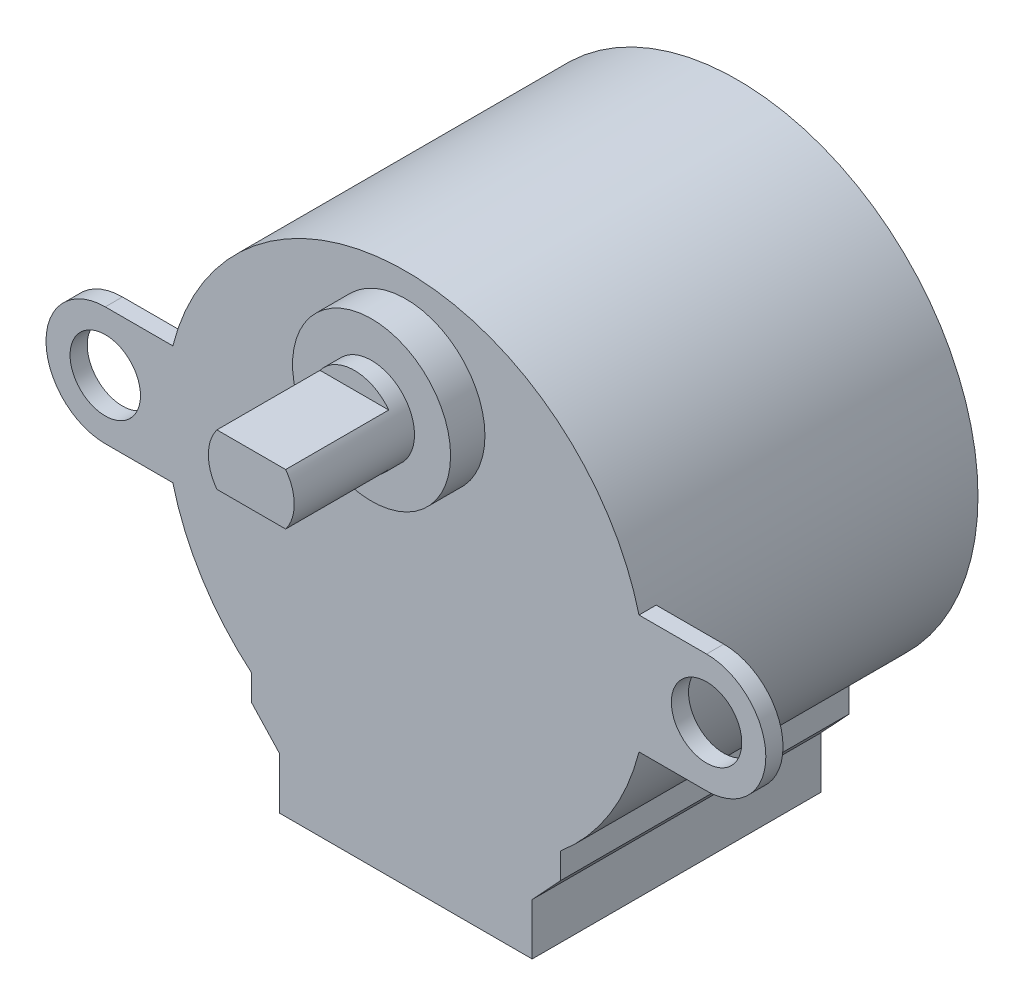
SolidWorks part; units mm, degrees
material "Air"
ref_plane "Front Plane" through (0, 0, 0) normal (0, 0, 1) x (1, 0, 0)
ref_plane "Top Plane" through (0, 0, 0) normal (0, 1, 0) x (1, 0, 0)
ref_plane "Right Plane" through (0, 0, 0) normal (1, 0, 0) x (0, 0, -1)
sketch "Sketch1" plane through (0, 0, 0) normal (0, 0, 1) x (1, 0, 0)
  circle A0 centre (0, 0) radius 14
  dimension "D1" = 28
extrude "Boss-Extrude1" add sketch "Sketch1" along normal blind 19.3
sketch "Sketch3" plane through (0, 0, 19.3) normal (0, 0, 1) x (1, 0, 0)
  line L0 (672.6511, 1264.4521) -> (697.6511, 1264.4521) construction
  line L1 (-576.9945, 40.9982) -> (-576.9945, 65.9982) construction
  dimension "D1" = 25
  dimension "D2" = 25
sketch "Sketch2" plane through (0, 0, 19.3) normal (0, 0, 1) x (1, 0, 0)
  line L0 (-7.35, -17) -> (7.35, -17)
  line L1 (7.35, -17) -> (7.35, -14)
  line L2 (7.35, -14) -> (9, -12.2238)
  line L3 (9, -12.2238) -> (9, -10.7238)
  line L4 (-7.35, -17) -> (-7.35, -14)
  line L5 (-7.35, -14) -> (-9, -12.2238)
  line L6 (-9, -12.2238) -> (-9, -10.7238)
  line L7 (9, -10.7238) -> (-9, -10.7238) construction
  circle A0 centre (0, 0) radius 14 construction
  arc A1 (-9, -10.7238) -> (9, -10.7238) centre (0, 0) ccw
  point P2 (0, -17)
  dimension "D1" = 14.7
  dimension "D2" = 17
  dimension "D3" = 18
  dimension "D4" = 3
  dimension "D5" = 3
  dimension "D6" = 1.5
  dimension "D7" = 1.5
extrude "Boss-Extrude2" add sketch "Sketch2" against normal blind 16.8 contours L1 L2 L3 A1 L6 L5 L4 L0
sketch "Sketch4" plane through (0, -17, 0) normal (0, -1, 0) x (1, 0, 0)
  line L0 (-3, 17.55) -> (3, 17.55) construction
  line L1 (-3, 18.05) -> (3, 18.05)
  line L2 (-3, 17.05) -> (3, 17.05)
  line L3 (-7.35, 19.3) -> (7.35, 19.3) construction
  arc A0 (-3, 18.05) -> (-3, 17.05) centre (-3, 17.55) ccw
  arc A1 (3, 17.05) -> (3, 18.05) centre (3, 17.55) ccw
  point P2 (0, 17.55)
  dimension "D1" = 6
  dimension "D2" = 0.5
  dimension "D3" = 1.75
extrude "Cut-Extrude1" cut sketch "Sketch4" against normal blind 2
sketch "Sketch5" plane through (0, 0, 19.3) normal (0, 0, 1) x (1, 0, 0)
  line L0 (0, 14) -> (0, -18.7354) construction
  line L1 (0, 0) -> (9.5563, 0) construction
  line L2 (-17.5, 3.45) -> (-13.5683, 3.45)
  line L3 (-17.5, -3.45) -> (-13.5683, -3.45)
  line L4 (17.5, -3.45) -> (13.5683, -3.45)
  line L5 (17.5, 3.45) -> (13.5683, 3.45)
  circle A0 centre (-17.5, 0) radius 2.05
  arc A3 (-17.5, 3.45) -> (-17.5, -3.45) centre (-17.5, 0) ccw
  arc A4 (9, -10.7238) -> (-9, -10.7238) centre (0, 0) ccw construction
  arc A5 (13.5683, 3.45) -> (13.5683, -3.45) centre (0, 0) cw
  arc A6 (-13.5683, 3.45) -> (-13.5683, -3.45) centre (0, 0) ccw
  arc A7 (17.5, 3.45) -> (17.5, -3.45) centre (17.5, 0) cw
  circle A8 centre (17.5, 0) radius 2.05
  dimension "D1" = 4.1
  dimension "D3" = 6.9
extrude "Boss-Extrude3" add sketch "Sketch5" against normal blind 1
sketch "Sketch6" plane through (0, 0, 19.3) normal (0, 0, 1) x (1, 0, 0)
  line L0 (-24.9917, 0) -> (30.299, 0) construction
  line L1 (0, 14.8773) -> (0, -18.0753) construction
  circle A0 centre (0, 8) radius 4.6
  dimension "D1" = 9.2
  dimension "D2" = 8
extrude "Boss-Extrude4" add sketch "Sketch6" along normal blind 2
sketch "Sketch7" plane through (0, 0, 21.3) normal (0, 0, 1) x (1, 0, 0)
  circle A0 centre (0, 8) radius 2.5
  dimension "D1" = 5
extrude "Boss-Extrude5" add sketch "Sketch7" along normal blind 7
sketch "Sketch8" plane through (0, 0, 28.3) normal (0, 0, 1) x (1, 0, 0)
  line L0 (-2, 9.5) -> (2, 9.5)
  line L1 (-2, 6.5) -> (2, 6.5)
  line L2 (0, 9.5) -> (0, 6.5) construction
  circle A0 centre (0, 8) radius 2.5
  point P9 (0, 8)
  circle M4 centre (0, 8) radius 2.5
  dimension "D2" = 5
  dimension "D1" = 3
extrude "Cut-Extrude2" cut sketch "Sketch8" against normal blind 6 contours L0 M4 | L1 M4
sketch "Sketch9" plane through (0, 0, 19.3) normal (0, 0, 1) x (1, 0, 0)
  line L11 (13.5683, -3.45) -> (17.5, -3.45)
  line L12 (17.5, 3.45) -> (13.5683, 3.45)
  line L13 (-13.5683, 3.45) -> (-17.5, 3.45)
  line L14 (-17.5, -3.45) -> (-13.5683, -3.45)
  line L15 (-9, -10.7238) -> (-9, -12.2238)
  line L16 (-9, -12.2238) -> (-7.35, -14)
  line L17 (-7.35, -14) -> (-7.35, -17)
  line L18 (-7.35, -17) -> (7.35, -17)
  line L19 (7.35, -17) -> (7.35, -14)
  line L20 (7.35, -14) -> (9, -12.2238)
  line L21 (9, -12.2238) -> (9, -10.7238)
  line L22 (13.5683, -3.45) -> (17.5, -3.45)
  line L23 (17.5, 3.45) -> (13.5683, 3.45)
  line L24 (-13.5683, 3.45) -> (-17.5, 3.45)
  line L25 (-17.5, -3.45) -> (-13.5683, -3.45)
  line L26 (-9, -10.7238) -> (-9, -12.2238)
  line L27 (-9, -12.2238) -> (-7.35, -14)
  line L28 (-7.35, -14) -> (-7.35, -17)
  line L29 (-7.35, -17) -> (7.35, -17)
  line L30 (7.35, -17) -> (7.35, -14)
  line L31 (7.35, -14) -> (9, -12.2238)
  line L32 (9, -12.2238) -> (9, -10.7238)
  arc A5 (9, -10.7238) -> (13.5683, -3.45) centre (0, 0) ccw
  arc A6 (17.5, -3.45) -> (17.5, 3.45) centre (17.5, 0) ccw
  arc A7 (13.5683, 3.45) -> (-13.5683, 3.45) centre (0, 0) ccw
  arc A8 (-17.5, 3.45) -> (-17.5, -3.45) centre (-17.5, 0) ccw
  arc A9 (-13.5683, -3.45) -> (-9, -10.7238) centre (0, 0) ccw
  arc A10 (9, -10.7238) -> (13.5683, -3.45) centre (0, 0) ccw
  arc A11 (17.5, -3.45) -> (17.5, 3.45) centre (17.5, 0) ccw
  arc A12 (13.5683, 3.45) -> (-13.5683, 3.45) centre (0, 0) ccw
  arc A13 (-17.5, 3.45) -> (-17.5, -3.45) centre (-17.5, 0) ccw
  arc A14 (-13.5683, -3.45) -> (-9, -10.7238) centre (0, 0) ccw
  dimension "D1" = 0
